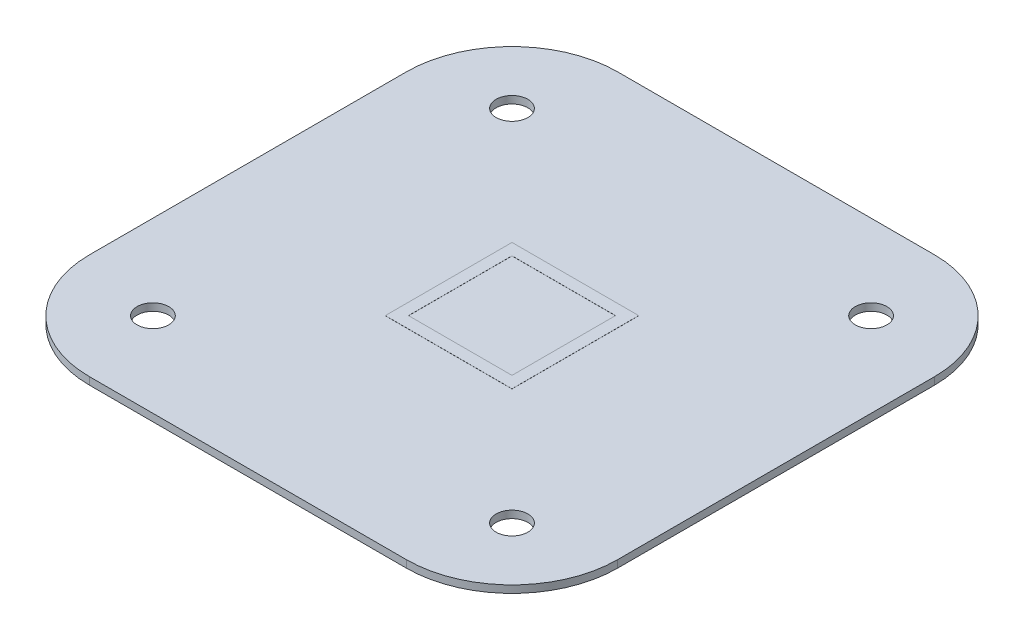
SolidWorks part; units mm, degrees
material "Glass"
ref_plane "Front Plane" through (0, 0, 0) normal (0, 0, 1) x (1, 0, 0)
ref_plane "Top Plane" through (0, 0, 0) normal (0, 1, 0) x (1, 0, 0)
ref_plane "Right Plane" through (0, 0, 0) normal (1, 0, 0) x (0, 0, -1)
sketch "Sketch1" plane through (0, 0, 0) normal (0, 1, 0) x (1, 0, 0)
  line L1 (17, -17) -> (-17, -17) construction
  line L2 (17, -17) -> (17, 17) construction
  line L3 (17, 17) -> (-17, 17) construction
  line L4 (-17, -17) -> (-17, 17) construction
  line L5 (17, -17) -> (-17, 17) construction
  line L6 (17, 17) -> (-17, -17) construction
  line L7 (25, -25) -> (-25, -25)
  line L8 (25, -25) -> (25, 25)
  line L9 (25, 25) -> (-25, 25)
  line L10 (-25, -25) -> (-25, 25)
  line L11 (25, -25) -> (-25, 25) construction
  line L12 (25, 25) -> (-25, -25) construction
  circle A0 centre (-17, 17) radius 1.5
  circle A1 centre (17, 17) radius 1.5
  circle A2 centre (17, -17) radius 1.5
  circle A3 centre (-17, -17) radius 1.5
  point P0 (0, 0)
  point P6 (0, 0)
  dimension "D1" = 3
  dimension "D2" = 34
  dimension "D3" = 50
extrude "Boss-Extrude1" add sketch "Sketch1" along normal blind 0.7
fillet "Fillet1" radius 10 4 edges at (-25, 0.35, -25) (25, 0.35, -25) (25, 0.35, 25) (-25, 0.35, 25)
sketch "Sketch2" plane through (0, 0.7, 0) normal (0, 1, 0) x (1, 0, 0)
  line L1 (4.9, -4.9) -> (-4.9, -4.9)
  line L2 (4.9, -4.9) -> (4.9, 4.9)
  line L3 (4.9, 4.9) -> (-4.9, 4.9)
  line L4 (-4.9, -4.9) -> (-4.9, 4.9)
  line L5 (4.9, -4.9) -> (-4.9, 4.9) construction
  line L6 (4.9, 4.9) -> (-4.9, -4.9) construction
  line L7 (6, -6) -> (-6, -6)
  line L8 (6, -6) -> (6, 6)
  line L9 (6, 6) -> (-6, 6)
  line L10 (-6, -6) -> (-6, 6)
  line L11 (6, -6) -> (-6, 6) construction
  line L12 (6, 6) -> (-6, -6) construction
  point P0 (0, 0)
  point P6 (0, 0)
  dimension "D1" = 1.1
  dimension "D2" = 12
extrude "Boss-Extrude2" add sketch "Sketch2" along normal blind 0.01
